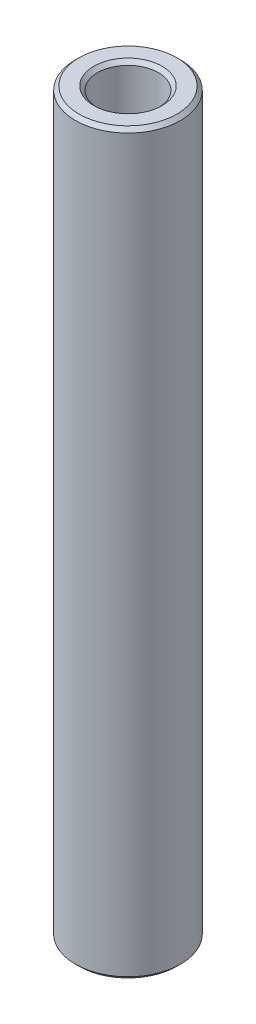
SolidWorks part; units mm, degrees
ref_plane "Ön Düzlem" through (0, 0, 0) normal (0, 0, 1) x (1, 0, 0)
ref_plane "Üst Düzlem" through (0, 0, 0) normal (0, 1, 0) x (1, 0, 0)
ref_plane "Sağ Düzlem" through (0, 0, 0) normal (1, 0, 0) x (0, 0, -1)
sketch "Çizim1" plane through (0, 0, 0) normal (0, 1, 0) x (1, 0, 0)
  circle A0 centre (0, 0) radius 1.65
  circle A1 centre (0, 0) radius 2.85
  dimension "D1" = 5.7
  dimension "D2" = 3.3
extrude "Yükseklik-Ekstrüzyon1" add sketch "Çizim1" along normal blind 40
chamfer "Pah1" distance 0.2 angle 45 4 edges at (0, 0, 1.65) (0, 0, 2.85) (0, 40, 1.65) (0, 40, 2.85)
